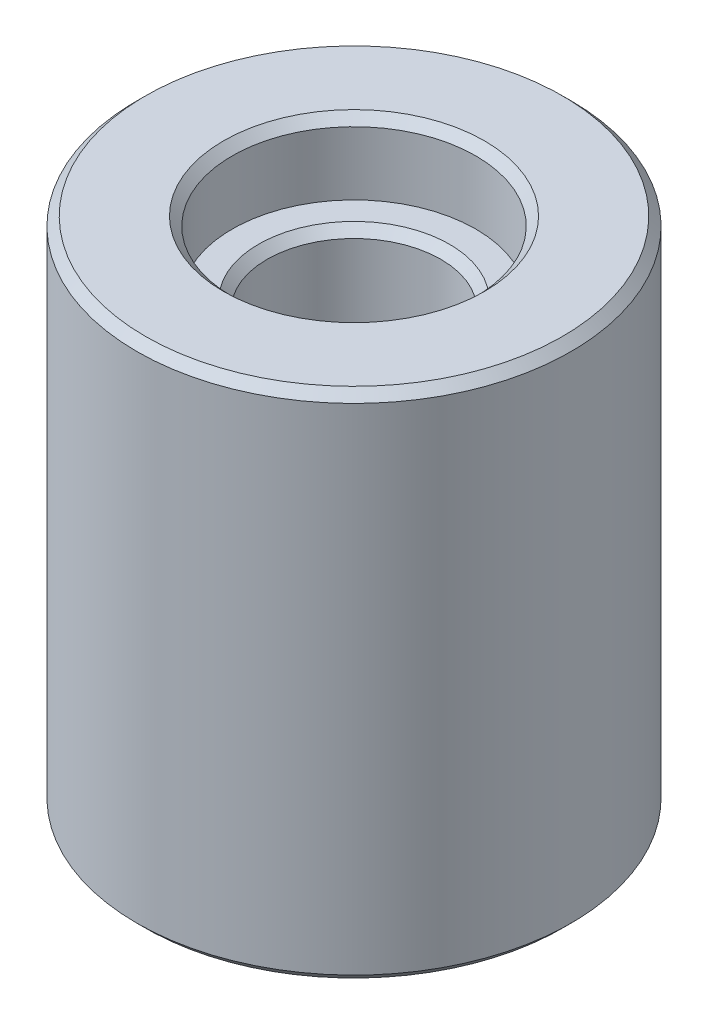
SolidWorks part; units mm, degrees
material "1060 slitina"
ref_plane "Přední rovina" through (0, 0, 0) normal (0, 0, 1) x (1, 0, 0)
ref_plane "Horní rovina" through (0, 0, 0) normal (0, 1, 0) x (1, 0, 0)
ref_plane "Pravá rovina" through (0, 0, 0) normal (1, 0, 0) x (0, 0, -1)
sketch "Skica1" plane through (0, 0, 0) normal (0, 0, 1) x (1, 0, 0)
  line L0 (0, 0) -> (0, -50000) construction
  line L1 (-25, 0) -> (-25, 59)
  line L2 (-25, 59) -> (-14.025, 59)
  line L3 (-14.025, 59) -> (-14.025, 50.7)
  line L4 (-14.025, 50.7) -> (-10, 50.7)
  line L5 (-10, 50.7) -> (-10, 11.9999)
  line L6 (-10, 11.9999) -> (-14.025, 11.9999)
  line L7 (-14.025, 11.9999) -> (-14.025, 3.9999)
  line L8 (-13.975, 0) -> (-25, 0)
  line L9 (-14.025, 3.9999) -> (-14.6, 3.9999)
  line L10 (-14.6, 3.9999) -> (-14.6, 2.6999)
  line L11 (-14.6, 2.6999) -> (-13.975, 2.6999)
  line L12 (-13.975, 2.6999) -> (-13.975, 0)
  dimension "D1" = 20
  dimension "D2" = 28.05
  dimension "D3" = 28.05
  dimension "D4" = 59
  dimension "D5" = 50
  dimension "D6" = 8.3
  dimension "D7" = 12
  dimension "D8" = 1.3
  dimension "D9" = 8
  dimension "D10" = 29.2
  dimension "D11" = 27.95
revolve "Rotovat1" add sketch "Skica1" angle 360 about L0
chamfer "Zkosení1" distance 1 angle 45 4 edges at (0, 59, 14.025) (0, 11.9999, 10) (0, 50.7, 10) (0, 0, 13.975)
sketch "Skica4" plane through (0, 0, 0) normal (0, -1, 0) x (1, 0, 0)
  circle A0 centre (0, 0) radius 19.5 construction
  circle A1 centre (0, 19.5) radius 3
  circle A2 centre (19.5, 0) radius 3
  circle A3 centre (0, -19.5) radius 3
  circle A4 centre (-19.5, 0) radius 3
  point P14 (0, 0)
  dimension "D1" = 39
  dimension "D2" = 6
  dimension "D3" = 4
sketch "Skica5" plane through (0, 0, 0) normal (0, -1, 0) x (-1, 0, 0)
  point P0 (0, 19.5)
  point P3 (19.5, 0)
  point P6 (0, -19.5)
  point P9 (-19.5, 0)
hole_wizard "M6 závit1" positions "Skica5" profile "Skica7" tap size "M6" standard "ISO"
sketch "Skica7" plane through (0, 0, -19.5) normal (1, 0, 0) x (0, 0, -1)
  line L0 (0, 0) -> (0, 13.5022)
  line L1 (0, 13.5022) -> (2.5, 12)
  line L2 (2.5, 12) -> (2.5, 0)
  line L5 (2.5, 0) -> (0, 0)
  line L10 (0, 13.5022) -> (-2.5, 12) construction
  line L11 (0, -6.35) -> (0, 107.95) construction
  dimension "Průměr závitníku" = 5
  dimension "Hloubka závitníku" = 12
  dimension "Úhel vrtání" = 118
cosmetic thread "Závit díry1" parameters "D1"=10, "D2"=6
cosmetic thread "Závit díry2" parameters "D1"=10, "D2"=6
cosmetic thread "Závit díry3" parameters "D1"=10, "D2"=6
cosmetic thread "Závit díry4" parameters "D1"=10, "D2"=6
chamfer "Zkosení2" distance 1 angle 45 2 edges at (0, 59, 25) (0, 0, 25)
chamfer "Zkosení3" distance 0.5 angle 45 4 edges at (0, 0, -22) (-19.5, 0, -2.5) (19.5, 0, -2.5) (0, 0, 17)
